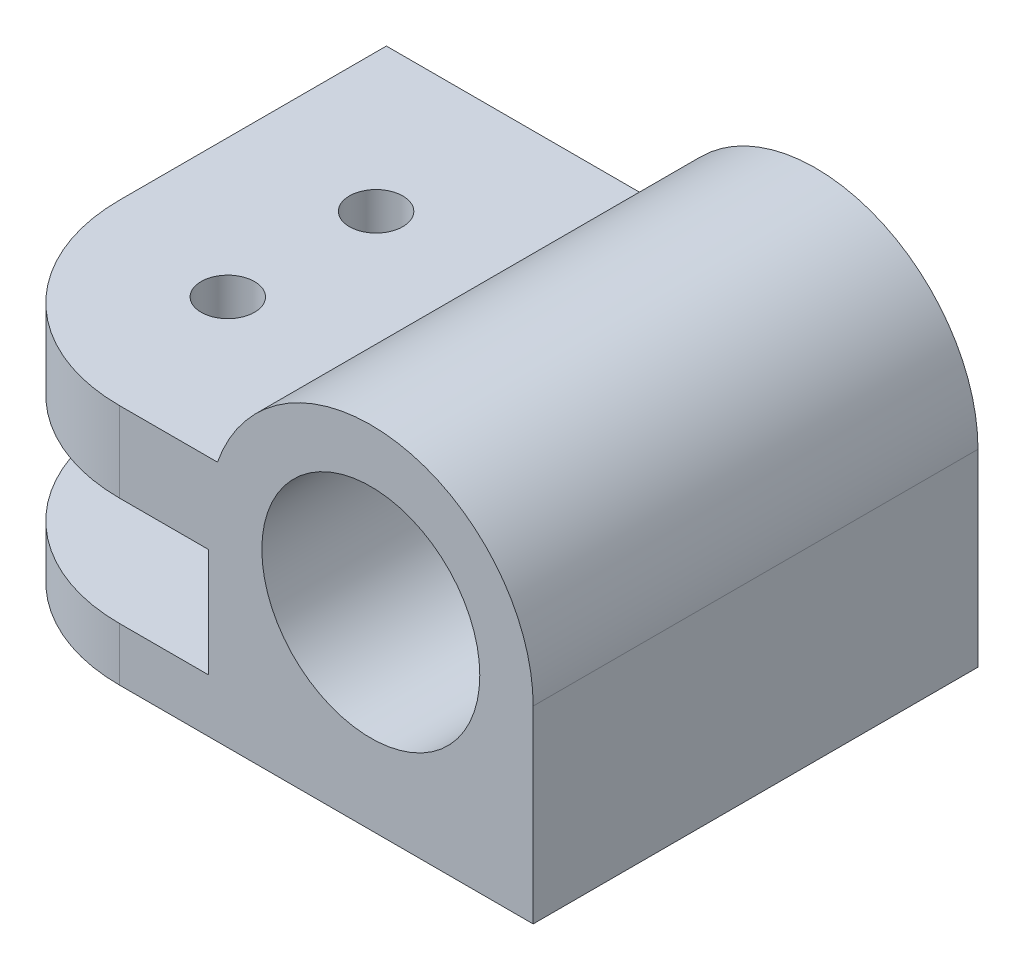
SolidWorks part; units mm, degrees
ref_plane "Plan de face" through (0, 0, 0) normal (0, 0, 1) x (1, 0, 0)
ref_plane "Plan de dessus" through (0, 0, 0) normal (0, 1, 0) x (1, 0, 0)
ref_plane "Plan de droite" through (0, 0, 0) normal (1, 0, 0) x (0, 0, -1)
sketch "Esquisse1" plane through (0, 0, 0) normal (0, 0, 1) x (1, 0, 0)
  line L0 (-9.125, 0) -> (-9.125, -10.6059)
  line L1 (-9.125, -10.6059) -> (9.125, -10.6059)
  line L3 (9.125, 0) -> (9.125, -10.6059)
  circle A0 centre (0, 0) radius 6.125
  circle A1 centre (0, 0) radius 9.125
  dimension "D1" = 12.25
  dimension "D2" = 3
extrude "Boss.-Extru.1" add sketch "Esquisse1" along normal blind 25
sketch "Esquisse13" plane through (0, -10.6059, 0) normal (0, -1, 0) x (1, 0, 0)
  line L1 (9.125, 0) -> (-24.125, 0)
  line L2 (9.125, 0) -> (9.125, 25)
  line L3 (9.125, 25) -> (-24.125, 25)
  line L4 (-24.125, 0) -> (-24.125, 25)
  line L5 (-9.125, 25) -> (-9.125, 0) construction
  dimension "D2" = 15
extrude "Boss.-Extru.10" add sketch "Esquisse13" against normal blind 3
sketch "Esquisse14" plane through (0, 0, 0) normal (0, 1, 0) x (1, 0, 0)
  line L1 (-24.125, 0) -> (-7.625, 0)
  line L2 (-24.125, 0) -> (-24.125, -25)
  line L7 (-9.125, -25) -> (9.125, -25) construction
  line L8 (-7.625, -25) -> (-7.625, 0)
  line L10 (-24.125, -25) -> (-7.625, -25)
  dimension "D2" = 16.5
extrude "Boss.-Extru.11" add sketch "Esquisse14" along normal blind 3 and the other way blind 1.5032
sketch "Esquisse15" plane through (0, 3, 0) normal (0, 1, 0) x (1, 0, 0)
  line L1 (-24.125, 0) -> (-24.125, -25) construction
  line L2 (-24.125, 0) -> (-8.6178, 0) construction
  circle A0 centre (-16.37, -8.3333) radius 1.5
  circle A1 centre (-16.37, -16.6667) radius 1.5
  dimension "D1" = 7.755
  dimension "D2" = 8.3333
  dimension "D3" = 8.3333
  dimension "D4" = 0
extrude "Enlèv. mat.-Extru.1" cut sketch "Esquisse15" against normal through all both and the other way through all
fillet "Congé1" radius 10 2 edges at (-24.125, 0.7484, 25) (-24.125, -9.1059, 25)
